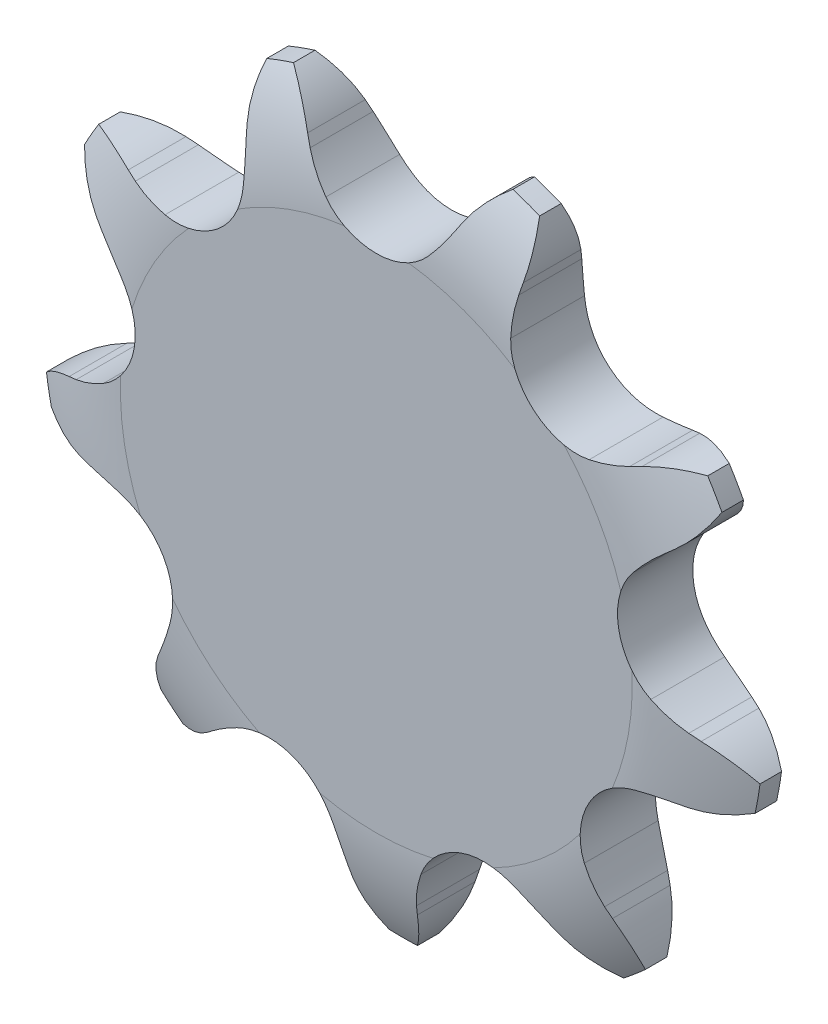
SolidWorks part; units mm, degrees
ref_plane "Front Plane" through (0, 0, 0) normal (0, 0, 1) x (1, 0, 0)
ref_plane "Top Plane" through (0, 0, 0) normal (0, 1, 0) x (1, 0, 0)
ref_plane "Right Plane" through (0, 0, 0) normal (1, 0, 0) x (0, 0, -1)
sketch "Sketch0" plane through (0, 0, 0) normal (0, 0, 1) x (1, 0, 0)
  line L0 (4, -10.9899) -> (0, 0) construction
  line L1 (0, 0) -> (10.1284, -5.8476) construction
  line L2 (0, 0) -> (-4, -10.9899) construction
  line L3 (4, -10.9899) -> (10.1284, -5.8476) construction
  line L4 (4, -10.9899) -> (-4, -10.9899) construction
  line L5 (6.6169, -9.7493) -> (6.322, -9.5008)
  line L6 (4, -10.9899) -> (0, -12.4458) construction
  line L7 (1.1979, -11.7217) -> (1.2641, -11.3417)
  line L8 (0, -10.9899) -> (0, -13.3899) construction
  line L9 (5.2105, -8.7449) -> (2.1016, -14.5107) construction
  line L10 (0, 0) -> (0, -10.9899) construction
  line L11 (6.322, -9.5008) -> (2.1016, -14.5107) construction
  line L12 (0, -13.3899) -> (0, -14.0161) construction
  line L13 (9.3623, -6.4904) -> (6.6169, -9.7493) construction
  circle A0 centre (0, 0) radius 13.3899 construction
  circle A1 centre (0, 0) radius 11.6952 construction
  arc A2 (-4.1222, -15.1007) -> (12.8643, -8.9181) centre (0, 0) ccw
  circle A3 centre (0, 0) radius 14.0161 construction
  circle A4 centre (4, -10.9899) radius 2.5 construction
  arc A7 (5.2105, -8.7449) -> (1.6296, -10.0482) centre (4, -10.9899) ccw
  circle A8 centre (4, -10.9899) radius 2.5506 construction
  arc A9 (6.6169, -9.7493) -> (12.8643, -8.9181) centre (9.3623, -6.4904) ccw
  arc A10 (6.322, -9.5008) -> (5.2105, -8.7449) centre (2.1016, -14.5107) ccw
  arc A11 (1.1979, -11.7217) -> (-4.1222, -15.1007) centre (-3, -10.9899) cw
  arc A12 (1.2641, -11.3417) -> (1.6296, -10.0482) centre (7.7174, -12.4667) cw
  dimension "D1" = 2.5506
  dimension "R" = 2.5506
sketch "Sketch1" plane through (0, 0, 0) normal (1, 0, 0) x (0, 0, -1)
  line L0 (1.4, 0) -> (-1.4, 0)
  line L1 (-1.4, 0) -> (-1.4, 9.5169)
  line L2 (-1.4, 11.6952) -> (0, 11.6952) construction
  line L3 (-0.4, 13.3899) -> (0.4, 13.3899)
  line L5 (1.4, 9.5169) -> (1.4, 0)
  line L7 (0, 13.3899) -> (0, 0) construction
  line L8 (-1.4, 9.5169) -> (1.4, 9.5169) construction
  line L9 (0, 13.3899) -> (0, -13.3899) construction
  line L10 (-1.4, 9.5169) -> (-1.4, 13.3899) construction
  line L11 (-1.4, 13.3899) -> (-0.4, 13.3899) construction
  line L12 (0.4, 13.3899) -> (1.4, 13.3899) construction
  line L13 (1.4, 13.3899) -> (1.4, 9.5169) construction
  line L14 (0, 0) -> (-6.4008, 0) construction
  line L15 (-1.4, 11.6952) -> (-1.4, 6.3952) construction
  line L22 (1.4, 0) -> (-10.6, 0) construction
  line L24 (-1.4, 0) -> (-1.4, 6.3952) construction
  arc A0 (-0.4, 13.3899) -> (-1.4, 9.5169) centre (6.6, 9.5169) ccw
  arc A1 (0.4, 13.3899) -> (1.4, 9.5169) centre (-6.6, 9.5169) cw
  dimension "R" = 8
revolve "Revolve1" add sketch "Sketch1" angle 360 mid plane about L0
extrude "Cut-Extrude1" cut sketch "Sketch0" against normal through all and the other way through all
pattern_circular "CirPattern1" count 9 over 360 about axis through (0, 0, 0) along (0, 0, 1) of "Cut-Extrude1"
sketch "Sketch2" plane through (0, 0, 0) normal (0, 0, 1) x (1, 0, 0)
  circle A0 centre (0, 0) radius 3 construction
  circle A1 centre (0, 0) radius 7.5
  circle A2 centre (0, 0) radius 13.39 construction
  dimension "Bore" = 6
  dimension "Hub Dia." = 15
  dimension "OD" = 26.78
extrude "Boss-Extrude1" add sketch "Sketch2" along normal up to vertex (10.6 mm away) from surface at 1.4 starting at face at (0, 0, 1.4)
sketch "Sketch3" plane through (0, 0, 0) normal (0, 0, 1) x (1, 0, 0)
  circle A0 centre (0, 0) radius 3 construction
  circle A1 centre (0, 0) radius 3
extrude "Cut-Extrude2" [suppressed] cut sketch "Sketch3" along normal through all and the other way through all
sketch "Sketch4" plane through (0, 0, 0) normal (1, 0, 0) x (0, 0, -1)
  line L0 (-10.6, 7.5) -> (-10.6, 7)
  line L1 (-1.4, 13.3899) -> (-3.5, 13.3899)
  line L2 (-1.4, 13.3899) -> (-1.4, 6.3952)
  line L3 (-1.4, 6.3952) -> (-3.5, 6.3952)
  line L4 (-3.5, 13.3899) -> (-3.5, 6.3952)
  line L9 (-10.6, 7) -> (-10.1, 7.5)
  line L10 (-10.1, 7.5) -> (-10.6, 7.5)
  dimension "C" = 0.5
  dimension "D3" = 2.1
revolve "Cut-Revolve1" cut sketch "Sketch4" angle 360 mid plane about L22
sketch "Sketch5" plane through (0, 0, 0) normal (0, 0, 1) x (1, 0, 0)
  circle A0 centre (0, 0) radius 13.39 construction
  circle A1 centre (0, 0) radius 13.39
extrude "Cut-Extrude3" [suppressed] cut sketch "Sketch5" against normal through all and the other way through all flip side to cut
sketch "Sketch6" plane through (0, 0, 1.4) normal (0, 0, 1) x (1, 0, 0)
  circle A0 centre (0, 0) radius 11
  dimension "D1" = 22
extrude "Cut-Extrude4" cut sketch "Sketch6" along normal blind 10
sketch "Sketch7" plane through (0, 0, 1.4) normal (0, 0, 1) x (1, 0, 0)
  line L0 (0, 9.1446) -> (5.878, 7.0052) construction
  arc A0 (-1.1946, 9.4417) -> (1.1946, 9.4417) centre (0, 11.6952) ccw construction
  arc A1 (5.1539, 8.0006) -> (6.9841, 6.4649) centre (7.5175, 8.9591) ccw construction
  circle A2 centre (0, 0) radius 8.5931 construction
  dimension "D1" = 17.1863
sketch "Sketch9" [suppressed] plane through (0, 0, 1.4) normal (0, 0, 1) x (1, 0, 0)
  line L0 (0, 0) -> (-5.35, 0) construction
  circle A0 centre (0, 0) radius 5.35 construction
  circle A1 centre (-5.35, 0) radius 1.2
  circle A7 centre (-2.675, 4.6332) radius 1.2
  circle A8 centre (2.675, 4.6332) radius 1.2
  circle A9 centre (5.35, 0) radius 1.2
  circle A10 centre (2.675, -4.6332) radius 1.2
  circle A11 centre (-2.675, -4.6332) radius 1.2
  dimension "D1" = 10.7
  dimension "D2" = 2.4
  dimension "D4" = 5.35
  dimension "D5" = 60
  dimension "D3" = 6
extrude "Cut-Extrude5" [suppressed] cut sketch "Sketch9" against normal blind 10
equation "\"360/N@Sketch0\" = 360/\"Teeth@CirPattern1\""
equation "\"Ds@Sketch0\" = 1.005 * \"Dr@Sketch0\" + ( 0.003 * 25.4 ) "
equation "\"R@Sketch0\" = 1/2 * \"Ds@Sketch0\""
equation "\"A@Sketch0\" = 35 +  ( 60 / \"Teeth@CirPattern1\" ) "
equation "\"B@Sketch0\" = 18 -  ( 56 / \"Teeth@CirPattern1\" )"
equation "\"ac@Sketch0\" = 0.8 * \"Dr@Sketch0\""
equation "\"ab@Sketch0\" = 1.4 * \"Dr@Sketch0\""
equation "\"J@Sketch0\" = 0.3 * \"Pitch@Sketch0\""
equation "\"D3@Sketch4\" = \"t@Sketch1\" * 3 / 4"
